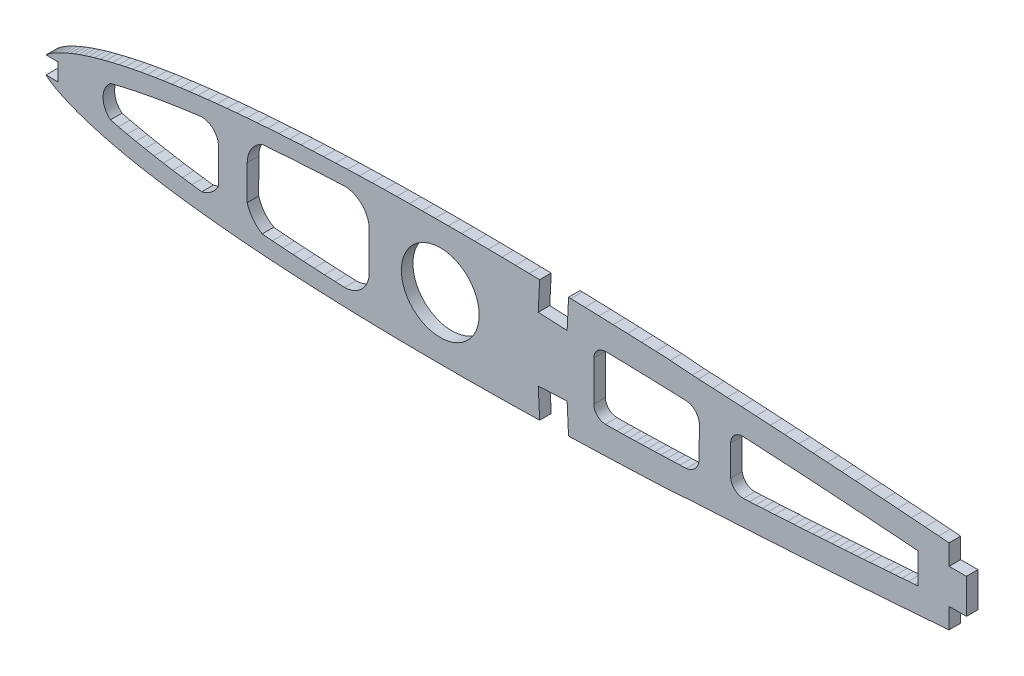
SolidWorks part; units mm, degrees
ref_plane "前视基准面" through (0, 0, 0) normal (0, 0, 1) x (1, 0, 0)
ref_plane "上视基准面" through (0, 0, 0) normal (0, 1, 0) x (1, 0, 0)
ref_plane "右视基准面" through (0, 0, 0) normal (1, 0, 0) x (0, 0, -1)
sketch "Model" plane through (0, 0, 0) normal (0, 0, 1) x (1, 0, 0)
  line L0 (13.461, 11.505) -> (15.502, 11.505)
  line L1 (15.502, 11.505) -> (15.502, 14.505)
  line L2 (15.502, 14.505) -> (13.4622, 14.505)
  line L3 (103.8128, 2.6102) -> (103.5687, 7.7226)
  line L4 (103.5687, 7.7226) -> (98.5737, 7.4806)
  line L5 (98.5737, 7.4806) -> (98.8157, 2.4866)
  line L6 (103.8047, 23.399) -> (103.8093, 23.2812)
  line L7 (103.8093, 23.2812) -> (103.5683, 18.2872)
  line L8 (103.5683, 18.2872) -> (98.5733, 18.5292)
  line L9 (98.5733, 18.5292) -> (98.8153, 23.5232)
  line L10 (169.612, 6.4807) -> (167.82, 6.3397)
  line L11 (167.82, 6.3397) -> (165.478, 6.1597)
  line L12 (165.478, 6.1597) -> (163.088, 5.9777)
  line L13 (163.088, 5.9777) -> (160.699, 5.7997)
  line L14 (160.699, 5.7997) -> (158.31, 5.6247)
  line L15 (158.31, 5.6247) -> (155.88, 5.4507)
  line L16 (155.88, 5.4507) -> (153.452, 5.2797)
  line L17 (153.452, 5.2797) -> (151.022, 5.1117)
  line L18 (151.022, 5.1117) -> (148.565, 4.9437)
  line L19 (148.565, 4.9437) -> (146.108, 4.7807)
  line L20 (146.108, 4.7807) -> (143.649, 4.6217)
  line L21 (143.649, 4.6217) -> (141.171, 4.4667)
  line L22 (141.171, 4.4667) -> (138.693, 4.3167)
  line L23 (138.693, 4.3167) -> (136.215, 4.1697)
  line L24 (136.215, 4.1697) -> (133.728, 4.0247)
  line L25 (133.728, 4.0247) -> (131.241, 3.8827)
  line L26 (131.241, 3.8827) -> (128.754, 3.7447)
  line L27 (128.754, 3.7447) -> (126.267, 3.6127)
  line L28 (126.267, 3.6127) -> (125.2039, 3.5589)
  line L29 (125.2039, 3.5589) -> (121.403, 3.255)
  line L30 (121.403, 3.255) -> (118.925, 3.147)
  line L31 (118.925, 3.147) -> (116.447, 3.043)
  line L32 (116.447, 3.043) -> (113.989, 2.946)
  line L33 (113.989, 2.946) -> (111.532, 2.855)
  line L34 (111.532, 2.855) -> (109.074, 2.77)
  line L35 (109.074, 2.77) -> (106.645, 2.692)
  line L36 (106.645, 2.692) -> (104.216, 2.621)
  line L37 (104.216, 2.621) -> (103.8128, 2.6102)
  line L38 (98.8157, 2.4866) -> (97.008, 2.448)
  line L39 (97.008, 2.448) -> (94.618, 2.404)
  line L40 (94.618, 2.404) -> (92.277, 2.369)
  line L41 (92.277, 2.369) -> (89.936, 2.341)
  line L42 (89.936, 2.341) -> (87.595, 2.321)
  line L43 (87.595, 2.321) -> (85.31, 2.309)
  line L44 (85.31, 2.309) -> (83.027, 2.305)
  line L45 (83.027, 2.305) -> (80.742, 2.309)
  line L46 (80.742, 2.309) -> (78.524, 2.321)
  line L47 (78.524, 2.321) -> (76.307, 2.341)
  line L48 (76.307, 2.341) -> (74.09, 2.371)
  line L49 (74.09, 2.371) -> (71.948, 2.408)
  line L50 (71.948, 2.408) -> (69.807, 2.455)
  line L51 (69.807, 2.455) -> (67.665, 2.511)
  line L52 (67.665, 2.511) -> (65.606, 2.574)
  line L53 (65.606, 2.574) -> (63.548, 2.647)
  line L54 (63.548, 2.647) -> (61.49, 2.73)
  line L55 (61.49, 2.73) -> (59.523, 2.818)
  line L56 (59.523, 2.818) -> (57.557, 2.917)
  line L57 (57.557, 2.917) -> (55.591, 3.027)
  line L58 (55.591, 3.027) -> (53.723, 3.142)
  line L59 (53.723, 3.142) -> (51.857, 3.267)
  line L60 (51.857, 3.267) -> (49.991, 3.405)
  line L61 (49.991, 3.405) -> (48.23, 3.545)
  line L62 (48.23, 3.545) -> (46.471, 3.697)
  line L63 (46.471, 3.697) -> (44.712, 3.861)
  line L64 (44.712, 3.861) -> (43.065, 4.026)
  line L65 (43.065, 4.026) -> (41.419, 4.202)
  line L66 (41.419, 4.202) -> (39.773, 4.391)
  line L67 (39.773, 4.391) -> (38.246, 4.579)
  line L68 (38.246, 4.579) -> (36.722, 4.78)
  line L69 (36.722, 4.78) -> (35.198, 4.995)
  line L70 (35.198, 4.995) -> (33.797, 5.205)
  line L71 (33.797, 5.205) -> (32.399, 5.429)
  line L72 (32.399, 5.429) -> (31.003, 5.667)
  line L73 (31.003, 5.667) -> (29.733, 5.898)
  line L74 (29.733, 5.898) -> (28.466, 6.142)
  line L75 (28.466, 6.142) -> (27.203, 6.402)
  line L76 (27.203, 6.402) -> (26.069, 6.65)
  line L77 (26.069, 6.65) -> (24.939, 6.914)
  line L78 (24.939, 6.914) -> (23.813, 7.193)
  line L79 (23.813, 7.193) -> (22.82, 7.455)
  line L80 (22.82, 7.455) -> (21.831, 7.732)
  line L81 (21.831, 7.732) -> (20.847, 8.028)
  line L82 (20.847, 8.028) -> (19.997, 8.3)
  line L83 (19.997, 8.3) -> (19.154, 8.591)
  line L84 (19.154, 8.591) -> (18.318, 8.902)
  line L85 (18.318, 8.902) -> (17.617, 9.183)
  line L86 (17.617, 9.183) -> (16.923, 9.481)
  line L87 (16.923, 9.481) -> (16.236, 9.796)
  line L88 (16.236, 9.796) -> (15.683, 10.066)
  line L89 (15.683, 10.066) -> (15.139, 10.354)
  line L90 (15.139, 10.354) -> (14.608, 10.666)
  line L91 (14.608, 10.666) -> (14.202, 10.931)
  line L92 (14.202, 10.931) -> (13.811, 11.216)
  line L93 (13.811, 11.216) -> (13.461, 11.505)
  line L94 (13.4622, 14.505) -> (13.811, 14.793)
  line L95 (13.811, 14.793) -> (14.202, 15.078)
  line L96 (14.202, 15.078) -> (14.608, 15.343)
  line L97 (14.608, 15.343) -> (15.139, 15.655)
  line L98 (15.139, 15.655) -> (15.683, 15.943)
  line L99 (15.683, 15.943) -> (16.236, 16.213)
  line L100 (16.236, 16.213) -> (16.923, 16.528)
  line L101 (16.923, 16.528) -> (17.617, 16.826)
  line L102 (17.617, 16.826) -> (18.318, 17.107)
  line L103 (18.318, 17.107) -> (19.154, 17.418)
  line L104 (19.154, 17.418) -> (19.997, 17.709)
  line L105 (19.997, 17.709) -> (20.847, 17.982)
  line L106 (20.847, 17.982) -> (21.831, 18.277)
  line L107 (21.831, 18.277) -> (22.82, 18.554)
  line L108 (22.82, 18.554) -> (23.813, 18.816)
  line L109 (23.813, 18.816) -> (24.939, 19.095)
  line L110 (24.939, 19.095) -> (26.069, 19.359)
  line L111 (26.069, 19.359) -> (27.203, 19.607)
  line L112 (27.203, 19.607) -> (28.466, 19.867)
  line L113 (28.466, 19.867) -> (29.733, 20.112)
  line L114 (29.733, 20.112) -> (31.003, 20.342)
  line L115 (31.003, 20.342) -> (32.399, 20.58)
  line L116 (32.399, 20.58) -> (33.797, 20.804)
  line L117 (33.797, 20.804) -> (35.198, 21.014)
  line L118 (35.198, 21.014) -> (36.722, 21.229)
  line L119 (36.722, 21.229) -> (38.246, 21.43)
  line L120 (38.246, 21.43) -> (39.773, 21.618)
  line L121 (39.773, 21.618) -> (41.419, 21.807)
  line L122 (41.419, 21.807) -> (43.065, 21.984)
  line L123 (43.065, 21.984) -> (44.712, 22.148)
  line L124 (44.712, 22.148) -> (46.471, 22.312)
  line L125 (46.471, 22.312) -> (48.23, 22.464)
  line L126 (48.23, 22.464) -> (49.991, 22.604)
  line L127 (49.991, 22.604) -> (51.857, 22.742)
  line L128 (51.857, 22.742) -> (53.723, 22.868)
  line L129 (53.723, 22.868) -> (55.591, 22.982)
  line L130 (55.591, 22.982) -> (57.557, 23.092)
  line L131 (57.557, 23.092) -> (59.523, 23.191)
  line L132 (59.523, 23.191) -> (61.49, 23.28)
  line L133 (61.49, 23.28) -> (63.548, 23.362)
  line L134 (63.548, 23.362) -> (65.606, 23.435)
  line L135 (65.606, 23.435) -> (67.665, 23.498)
  line L136 (67.665, 23.498) -> (69.807, 23.554)
  line L137 (69.807, 23.554) -> (71.948, 23.601)
  line L138 (71.948, 23.601) -> (74.09, 23.638)
  line L139 (74.09, 23.638) -> (76.307, 23.668)
  line L140 (76.307, 23.668) -> (78.524, 23.688)
  line L141 (78.524, 23.688) -> (80.742, 23.7)
  line L142 (80.742, 23.7) -> (83.027, 23.704)
  line L143 (83.027, 23.704) -> (85.31, 23.7)
  line L144 (85.31, 23.7) -> (87.595, 23.688)
  line L145 (87.595, 23.688) -> (89.936, 23.668)
  line L146 (89.936, 23.668) -> (92.277, 23.641)
  line L147 (92.277, 23.641) -> (94.618, 23.605)
  line L148 (94.618, 23.605) -> (97.008, 23.561)
  line L149 (97.008, 23.561) -> (98.8153, 23.5232)
  line L150 (103.8047, 23.399) -> (104.216, 23.388)
  line L151 (104.216, 23.388) -> (106.645, 23.317)
  line L152 (106.645, 23.317) -> (109.074, 23.239)
  line L153 (109.074, 23.239) -> (111.532, 23.154)
  line L154 (111.532, 23.154) -> (113.989, 23.063)
  line L155 (113.989, 23.063) -> (116.447, 22.966)
  line L156 (116.447, 22.966) -> (118.925, 22.863)
  line L157 (118.925, 22.863) -> (121.403, 22.754)
  line L158 (121.403, 22.754) -> (125.2037, 22.4456)
  line L159 (125.2037, 22.4456) -> (126.267, 22.3917)
  line L160 (126.267, 22.3917) -> (128.754, 22.2597)
  line L161 (128.754, 22.2597) -> (131.241, 22.1217)
  line L162 (131.241, 22.1217) -> (133.728, 21.9797)
  line L163 (133.728, 21.9797) -> (136.215, 21.8347)
  line L164 (136.215, 21.8347) -> (138.693, 21.6877)
  line L165 (138.693, 21.6877) -> (141.171, 21.5377)
  line L166 (141.171, 21.5377) -> (143.649, 21.3827)
  line L167 (143.649, 21.3827) -> (146.108, 21.2237)
  line L168 (146.108, 21.2237) -> (148.565, 21.0607)
  line L169 (148.565, 21.0607) -> (151.022, 20.8937)
  line L170 (151.022, 20.8937) -> (153.452, 20.7247)
  line L171 (153.452, 20.7247) -> (155.88, 20.5537)
  line L172 (155.88, 20.5537) -> (158.31, 20.3797)
  line L173 (158.31, 20.3797) -> (160.699, 20.2047)
  line L174 (160.699, 20.2047) -> (163.088, 20.0267)
  line L175 (163.088, 20.0267) -> (165.478, 19.8447)
  line L176 (165.478, 19.8447) -> (167.82, 19.6647)
  line L177 (167.82, 19.6647) -> (169.612, 19.5246)
  line L178 (24.5983, 15.8127) -> (26.008, 16.1651)
  line L179 (26.008, 16.1651) -> (27.4953, 16.5087)
  line L180 (27.4953, 16.5087) -> (28.9978, 16.8329)
  line L181 (28.9978, 16.8329) -> (30.5564, 17.1446)
  line L182 (30.5564, 17.1446) -> (32.1343, 17.4396)
  line L183 (32.1343, 17.4396) -> (33.7495, 17.7227)
  line L184 (33.7495, 17.7227) -> (35.3692, 17.9861)
  line L185 (35.3692, 17.9861) -> (37.0298, 18.2368)
  line L186 (37.0298, 18.2368) -> (38.7015, 18.4738)
  line L187 (38.7015, 18.4738) -> (40.3969, 18.6986)
  line L188 (50.8291, 19.7877) -> (52.6041, 19.9295)
  line L189 (52.6041, 19.9295) -> (54.3954, 20.0641)
  line L190 (54.3954, 20.0641) -> (56.1817, 20.1883)
  line L191 (56.1817, 20.1883) -> (57.9834, 20.3026)
  line L192 (57.9834, 20.3026) -> (59.7939, 20.4097)
  line L193 (59.7939, 20.4097) -> (61.6045, 20.5089)
  line L194 (61.6045, 20.5089) -> (63.423, 20.5982)
  line L195 (63.423, 20.5982) -> (65.096, 20.6754)
  line L196 (69.3469, 16.3491) -> (69.3469, 9.8278)
  line L197 (65.096, 5.5016) -> (63.423, 5.5788)
  line L198 (63.423, 5.5788) -> (61.6045, 5.6681)
  line L199 (61.6045, 5.6681) -> (59.7939, 5.7672)
  line L200 (59.7939, 5.7672) -> (57.9834, 5.8743)
  line L201 (57.9834, 5.8743) -> (56.1817, 5.9887)
  line L202 (56.1817, 5.9887) -> (54.3954, 6.1128)
  line L203 (54.3954, 6.1128) -> (52.6041, 6.2475)
  line L204 (52.6041, 6.2475) -> (50.8291, 6.3893)
  line L205 (40.3969, 7.4784) -> (38.7015, 7.7031)
  line L206 (38.7015, 7.7031) -> (37.0298, 7.9402)
  line L207 (37.0298, 7.9402) -> (35.3692, 8.1909)
  line L208 (35.3692, 8.1909) -> (33.7495, 8.4543)
  line L209 (33.7495, 8.4543) -> (32.1343, 8.7374)
  line L210 (32.1343, 8.7374) -> (30.5564, 9.0323)
  line L211 (30.5564, 9.0323) -> (28.9978, 9.3441)
  line L212 (28.9978, 9.3441) -> (27.4953, 9.6683)
  line L213 (27.4953, 9.6683) -> (26.008, 10.0119)
  line L214 (26.008, 10.0119) -> (24.5983, 10.3643)
  line L215 (169.612, 10.005) -> (169.612, 6.4807)
  line L217 (169.612, 10.005) -> (172.612, 10.005)
  line L218 (172.612, 10.005) -> (172.612, 16.005)
  line L219 (172.612, 16.005) -> (169.612, 16.005)
  line L220 (169.612, 16.005) -> (169.612, 19.5246)
  line L221 (164.2298, 15.6309) -> (163.6779, 15.6741)
  line L222 (163.6779, 15.6741) -> (162.5805, 15.7588)
  line L223 (162.5805, 15.7588) -> (161.4815, 15.8425)
  line L224 (161.4815, 15.8425) -> (160.3787, 15.9253)
  line L225 (160.3787, 15.9253) -> (159.2778, 16.0092)
  line L226 (159.2778, 16.0092) -> (158.1806, 16.0904)
  line L227 (158.1806, 16.0904) -> (157.0797, 16.1706)
  line L228 (157.0797, 16.1706) -> (155.9787, 16.2509)
  line L229 (155.9787, 16.2509) -> (154.8809, 16.3298)
  line L230 (154.8809, 16.3298) -> (153.7801, 16.4077)
  line L231 (153.7801, 16.4077) -> (152.682, 16.4855)
  line L232 (152.682, 16.4855) -> (151.5842, 16.5608)
  line L233 (151.5842, 16.5608) -> (150.4834, 16.6363)
  line L234 (150.4834, 16.6363) -> (149.3855, 16.7104)
  line L235 (149.3855, 16.7104) -> (148.2877, 16.7834)
  line L236 (148.2877, 16.7834) -> (147.1897, 16.8551)
  line L237 (147.1897, 16.8551) -> (146.0931, 16.9257)
  line L238 (146.0931, 16.9257) -> (144.9954, 16.995)
  line L239 (144.9954, 16.995) -> (143.8957, 17.0633)
  line L240 (143.8957, 17.0633) -> (142.799, 17.1315)
  line L241 (142.799, 17.1315) -> (141.7031, 17.1971)
  line L242 (141.7031, 17.1971) -> (140.6045, 17.2618)
  line L243 (140.6045, 17.2618) -> (139.5079, 17.3264)
  line L244 (139.5079, 17.3264) -> (138.4132, 17.3885)
  line L245 (138.4132, 17.3885) -> (137.3166, 17.4495)
  line L246 (137.3166, 17.4495) -> (136.22, 17.5093)
  line L247 (136.22, 17.5093) -> (135.1253, 17.5678)
  line L248 (135.1253, 17.5678) -> (134.0287, 17.624)
  line L249 (124.1413, 18.0745) -> (121.9882, 18.1545)
  line L250 (121.9882, 18.1545) -> (120.8958, 18.1927)
  line L251 (120.8958, 18.1927) -> (119.8035, 18.2297)
  line L252 (119.8035, 18.2297) -> (118.7113, 18.2643)
  line L253 (118.7113, 18.2643) -> (117.6171, 18.2978)
  line L254 (117.6171, 18.2978) -> (116.5267, 18.3299)
  line L255 (116.5267, 18.3299) -> (115.4375, 18.3585)
  line L256 (115.4375, 18.3585) -> (114.3444, 18.386)
  line L257 (114.3444, 18.386) -> (113.2546, 18.4123)
  line L258 (113.2546, 18.4123) -> (112.1654, 18.4361)
  line L259 (112.1654, 18.4361) -> (111.0775, 18.4576)
  line L260 (111.0775, 18.4576) -> (110.2262, 18.4725)
  line L261 (108.1911, 16.4728) -> (108.1911, 9.5738)
  line L262 (110.1911, 7.5738) -> (112.1661, 7.5738)
  line L263 (112.1661, 7.5738) -> (113.2546, 7.5977)
  line L264 (113.2546, 7.5977) -> (114.3444, 7.6239)
  line L265 (114.3444, 7.6239) -> (115.4375, 7.6514)
  line L266 (115.4375, 7.6514) -> (116.5267, 7.68)
  line L267 (116.5267, 7.68) -> (117.6171, 7.7122)
  line L268 (117.6171, 7.7122) -> (118.7113, 7.7457)
  line L269 (118.7113, 7.7457) -> (119.8035, 7.7803)
  line L270 (119.8035, 7.7803) -> (120.8958, 7.8173)
  line L271 (120.8958, 7.8173) -> (121.9882, 7.8555)
  line L272 (121.9882, 7.8555) -> (123.0816, 7.8961)
  line L273 (123.0816, 7.8961) -> (124.1739, 7.9379)
  line L274 (134.0287, 8.386) -> (135.1253, 8.4422)
  line L275 (135.1253, 8.4422) -> (136.22, 8.5007)
  line L276 (136.22, 8.5007) -> (137.3166, 8.5605)
  line L277 (137.3166, 8.5605) -> (138.4132, 8.6215)
  line L278 (138.4132, 8.6215) -> (139.5079, 8.6836)
  line L279 (139.5079, 8.6836) -> (140.6045, 8.7481)
  line L280 (140.6045, 8.7481) -> (141.7031, 8.8128)
  line L281 (141.7031, 8.8128) -> (142.799, 8.8785)
  line L282 (142.799, 8.8785) -> (143.8957, 8.9467)
  line L283 (143.8957, 8.9467) -> (144.9954, 9.0149)
  line L284 (144.9954, 9.0149) -> (146.0931, 9.0843)
  line L285 (146.0931, 9.0843) -> (147.1897, 9.1548)
  line L286 (147.1897, 9.1548) -> (148.2877, 9.2266)
  line L287 (148.2877, 9.2266) -> (149.3855, 9.2996)
  line L288 (149.3855, 9.2996) -> (150.4834, 9.3737)
  line L289 (150.4834, 9.3737) -> (151.5842, 9.4492)
  line L290 (151.5842, 9.4492) -> (152.682, 9.5245)
  line L291 (152.682, 9.5245) -> (153.7801, 9.6023)
  line L292 (153.7801, 9.6023) -> (154.8809, 9.6801)
  line L293 (154.8809, 9.6801) -> (155.9787, 9.759)
  line L294 (155.9787, 9.759) -> (157.0797, 9.8393)
  line L295 (157.0797, 9.8393) -> (158.1806, 9.9196)
  line L296 (158.1806, 9.9196) -> (159.2778, 10.0008)
  line L297 (159.2778, 10.0008) -> (160.3787, 10.0846)
  line L298 (160.3787, 10.0846) -> (161.4815, 10.1674)
  line L299 (161.4815, 10.1674) -> (162.5805, 10.2511)
  line L300 (162.5805, 10.2511) -> (163.6779, 10.3359)
  line L301 (163.6779, 10.3359) -> (164.2269, 10.3789)
  line L302 (164.2298, 15.6309) -> (164.2269, 10.3789)
  line L303 (126.3866, 10.5271) -> (126.4343, 15.565)
  line L304 (131.8386, 15.565) -> (131.8386, 10.312)
  line L305 (43.2886, 15.756) -> (43.2886, 9.7801)
  line L306 (48.2546, 15.7744) -> (48.2425, 9.7801)
  arc A0 (24.5983, 15.8127) -> (24.5983, 10.3643) centre (26.8803, 13.0885) ccw
  circle A1 centre (81.6332, 13.005) radius 6.7257
  arc A2 (40.3969, 7.4784) -> (43.2886, 9.7801) centre (39.4286, 11.6622) ccw
  arc A3 (48.2425, 9.7801) -> (50.8291, 6.3893) centre (53.9052, 11.4178) ccw
  arc A4 (50.8291, 19.7877) -> (48.2546, 15.7744) centre (52.6981, 15.7563) ccw
  arc A5 (43.2886, 15.756) -> (40.3969, 18.6986) centre (40.3208, 15.7316) ccw
  arc A6 (126.4343, 15.565) -> (124.1413, 18.0745) centre (123.9734, 15.6187) ccw
  arc A7 (134.0287, 17.624) -> (131.8386, 15.565) centre (133.928, 15.5368) ccw
  arc A8 (124.1739, 7.9379) -> (126.3866, 10.5271) centre (123.8632, 10.4434) ccw
  arc A9 (131.8386, 10.312) -> (134.0287, 8.386) centre (134.009, 10.5718) ccw
  arc A10 (69.3469, 16.3491) -> (65.096, 20.6754) centre (65.02, 16.3491) ccw
  arc A11 (65.096, 5.5016) -> (69.3469, 9.8278) centre (65.02, 9.8278) ccw
  arc A12 (110.2262, 18.4725) -> (108.1911, 16.4728) centre (110.1911, 16.4728) ccw
  arc A13 (108.1911, 9.5738) -> (110.1911, 7.5738) centre (110.1911, 9.5738) ccw
  point P13 (103.7878, 23.399)
  point P19 (169.612, 6.4987)
  point P25 (0, 0)
  point P49 (0, 0)
  point P254 (164.2298, 15.655)
  point P255 (126.4528, 15.565)
  point P260 (164.2298, 10.3789)
  point P340 (48.2546, 15.7925)
  point P342 (0, 0)
  point P344 (124.1413, 18.0909)
  point P345 (126.4104, 10.5271)
  point P346 (103.8093, 2.6102)
extrude "凸台-拉伸1" add sketch "Model" along normal blind 2
